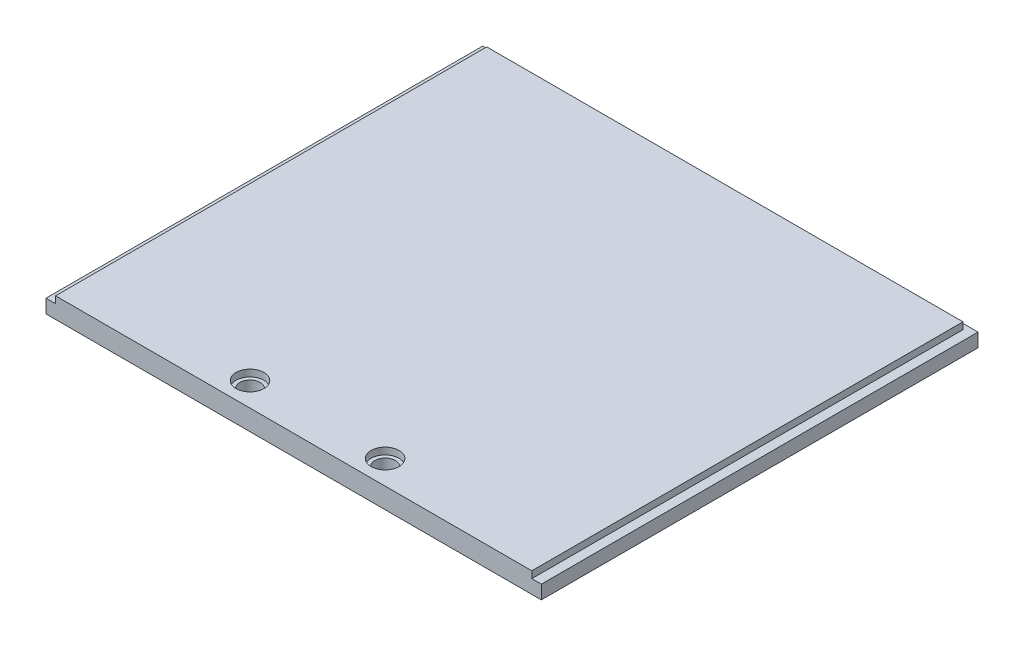
SolidWorks part; units mm, degrees
ref_plane "Front Plane" through (0, 0, 0) normal (0, 0, 1) x (1, 0, 0)
ref_plane "Top Plane" through (0, 0, 0) normal (0, 1, 0) x (1, 0, 0)
ref_plane "Right Plane" through (0, 0, 0) normal (1, 0, 0) x (0, 0, -1)
sketch "Sketch1" plane through (0, 0, 0) normal (0, 1, 0) x (1, 0, 0)
  line L1 (0, 0) -> (72.6, 0)
  line L2 (0, 0) -> (0, 64)
  line L3 (0, 64) -> (72.6, 64)
  line L4 (72.6, 0) -> (72.6, 64)
  dimension "D1" = 72.6
  dimension "D2" = 64
extrude "Boss-Extrude1" add sketch "Sketch1" along normal blind 2
sketch "Sketch2" plane through (0, 2, 0) normal (0, 1, 0) x (1, 0, 0)
  line L0 (0, 0) -> (72.6, 0) construction
  line L1 (1.4, 0) -> (71.2, 0)
  line L2 (1.4, 0) -> (1.4, 63.2)
  line L3 (1.4, 63.2) -> (71.2, 63.2)
  line L4 (71.2, 0) -> (71.2, 63.2)
  line L5 (0, 64) -> (0, 0) construction
  line L6 (72.6, 64) -> (0, 64) construction
  line L7 (72.6, 0) -> (72.6, 64) construction
  dimension "D1" = 1.4
  dimension "D2" = 0.8
  dimension "D3" = 1.4
extrude "Boss-Extrude2" add sketch "Sketch2" along normal blind 1
hole_wizard "Hole1" positions "Sketch3" profile "Sketch4" legacy end condition through all
sketch "Sketch3" plane through (0, 3, 0) normal (0, 1, 0) x (1, 0, 0)
  line L4 (1.4, 0) -> (71.2, 0) construction
  line L5 (1.4, 63.2) -> (1.4, 0) construction
  line L6 (71.2, 0) -> (71.2, 63.2) construction
  point P0 (26.4, 3.5)
  point P2 (46.2, 3.5)
  dimension "D1" = 25
  dimension "D2" = 25
  dimension "D3" = 3.5
sketch "Sketch4" plane through (26.4, 3, -3.5) normal (1, 0, 0) x (0, 0, 1)
  line L0 (0, 0) -> (0, 3)
  line L1 (0, 3) -> (1.5, 3)
  line L2 (1.5, 3) -> (1.5, 1)
  line L3 (1.5, 1) -> (2.05, 1)
  line L4 (2.05, 1) -> (2.05, 0)
  line L5 (2.05, 0) -> (0, 0)
  line L6 (0, 110) -> (0, -10) construction
  dimension "Diameter" = 3
  dimension "Depth" = 3
  dimension "C-Bore Diameter" = 4.1
  dimension "C-Bore Depth" = 1
